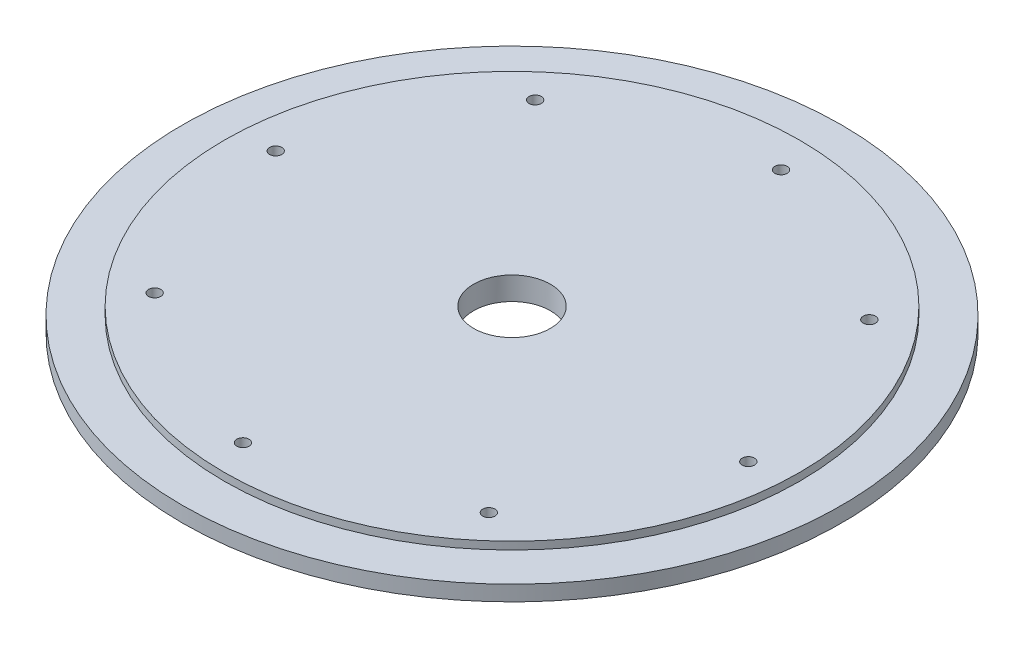
SolidWorks part; units mm, degrees
ref_plane "前视基准面" through (0, 0, 0) normal (0, 0, 1) x (1, 0, 0)
ref_plane "上视基准面" through (0, 0, 0) normal (0, 1, 0) x (1, 0, 0)
ref_plane "右视基准面" through (0, 0, 0) normal (1, 0, 0) x (0, 0, -1)
sketch "草图1" plane through (0, 0, 0) normal (0, 1, 0) x (1, 0, 0)
  circle A0 centre (0, 0) radius 43
  dimension "D1" = 86
extrude "凸台-拉伸1" add sketch "草图1" along normal blind 1
sketch "草图2" plane through (0, 1, 0) normal (0, 1, 0) x (1, 0, 0)
  circle A0 centre (0, 0) radius 37.5
  dimension "D1" = 75
extrude "凸台-拉伸2" add sketch "草图2" along normal blind 1
sketch "草图3" plane through (0, 2, 0) normal (0, 1, 0) x (1, 0, 0)
  circle A0 centre (0, 0) radius 5
  dimension "D1" = 10
extrude "切除-拉伸1" cut sketch "草图3" against normal blind 50
sketch "草图4" plane through (0, 0, 0) normal (0, -1, 0) x (1, 0, 0)
  circle A0 centre (0, 0) radius 5
  circle A1 centre (0, 0) radius 43
extrude "凸台-拉伸3" add sketch "草图4" along normal blind 1
sketch "草图5" plane through (0, -1, 0) normal (0, -1, 0) x (1, 0, 0)
  circle A0 centre (0, 0) radius 42.95
  circle A1 centre (0, 0) radius 43 construction
  dimension "D1" = 0.05
extrude "切除-拉伸2" cut sketch "草图5" against normal blind 500 flip side to cut
sketch "草图6" plane through (0, -1, 0) normal (0, -1, 0) x (1, 0, 0)
  circle A0 centre (24.7944, -21.777) radius 0.8
extrude "切除-拉伸3" cut sketch "草图6" against normal blind 500
pattern_circular "阵列(圆周)1" count 8 over 360 about axis through (0, 0, 0) along (0, 1, 0) of "切除-拉伸3"
